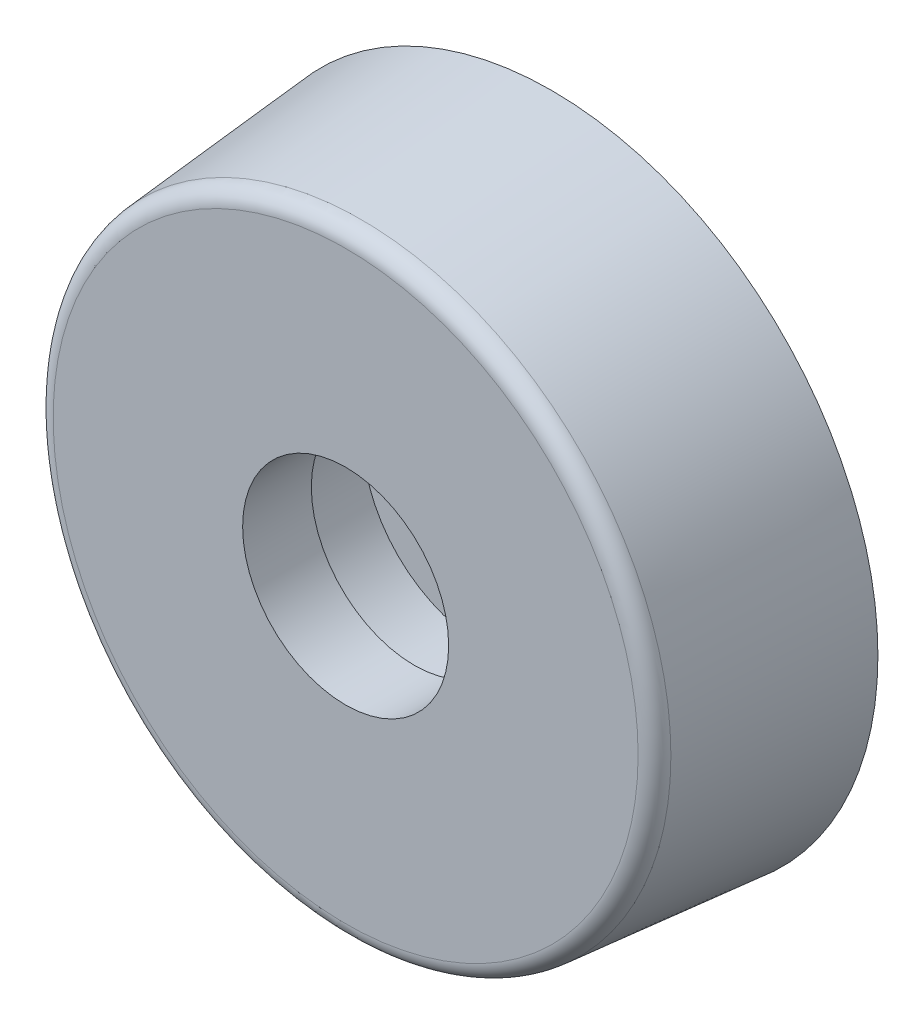
SolidWorks part; units mm, degrees
ref_plane "Спереди" through (0, 0, 0) normal (0, 0, 1) x (1, 0, 0)
ref_plane "Сверху" through (0, 0, 0) normal (0, 1, 0) x (1, 0, 0)
ref_plane "Справа" through (0, 0, 0) normal (1, 0, 0) x (0, 0, -1)
sketch "Эскиз1" plane through (0, 0, 0) normal (0, 0, 1) x (1, 0, 0)
  circle A0 centre (0, 0) radius 9.5
  dimension "D1" = 19
extrude "Бобышка-Вытянуть1" add sketch "Эскиз1" along normal blind 6 draft 5
sketch "Эскиз2" plane through (0, 0, 0) normal (0, 0, -1) x (-1, 0, 0)
  circle A0 centre (0, 0) radius 8
  circle A1 centre (0, 0) radius 4.5
  dimension "D1" = 16
  dimension "D2" = 9
extrude "Вырез-Вытянуть2" cut sketch "Эскиз2" against normal blind 3
sketch "Эскиз3" plane through (0, 0, 6) normal (0, 0, 1) x (1, 0, 0)
  circle A0 centre (0, 0) radius 3.5
  dimension "D1" = 7
extrude "Вырез-Вытянуть3" cut sketch "Эскиз3" against normal blind 4
sketch "Эскиз4" plane through (0, 0, 6) normal (0, 0, 1) x (1, 0, 0)
  circle A0 centre (0, 0) radius 3.55
  circle A1 centre (0, 0) radius 3
  dimension "D1" = 6
  dimension "D2" = 7.1
extrude "Бобышка-Вытянуть2" add sketch "Эскиз4" against normal blind 2
fillet "Скругление1" radius 0.5 1 edges at (8.9751, 0, 6)
